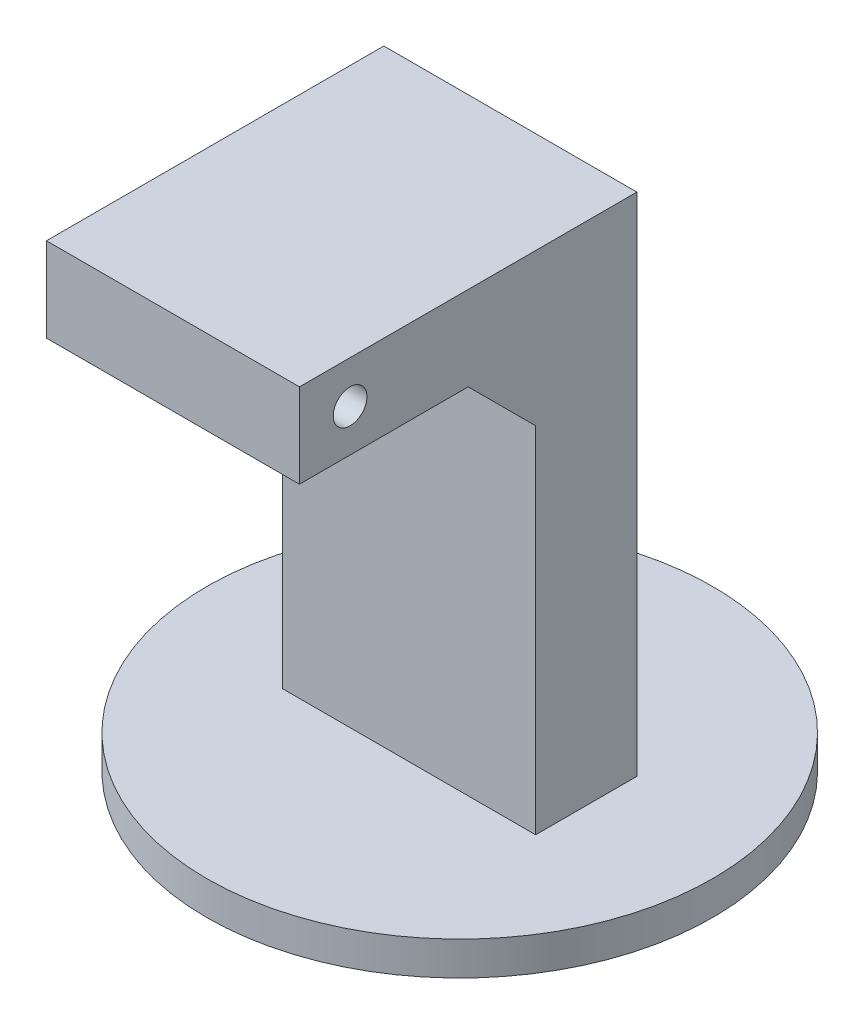
SolidWorks part; units mm, degrees
ref_plane "Front Plane" through (0, 0, 0) normal (0, 0, 1) x (1, 0, 0)
ref_plane "Top Plane" through (0, 0, 0) normal (0, 1, 0) x (1, 0, 0)
ref_plane "Right Plane" through (0, 0, 0) normal (1, 0, 0) x (0, 0, -1)
sketch "Sketch1" plane through (0, 0, 0) normal (0, 1, 0) x (1, 0, 0)
  circle A0 centre (0, 0) radius 15
  point P0 (0, 0)
  dimension "D1" = 30
extrude "Boss-Extrude1" add sketch "Sketch1" along normal blind 2
sketch "Sketch2" plane through (0, 2, 0) normal (0, 1, 0) x (1, 0, 0)
  line L1 (7.5, -3) -> (-7.5, -3)
  line L2 (7.5, -3) -> (7.5, 3)
  line L3 (7.5, 3) -> (-7.5, 3)
  line L4 (-7.5, -3) -> (-7.5, 3)
  line L5 (7.5, -3) -> (-7.5, 3) construction
  line L6 (7.5, 3) -> (-7.5, -3) construction
  point P0 (0, 0)
  dimension "D1" = 15
  dimension "D2" = 6
extrude "Boss-Extrude2" add sketch "Sketch2" along normal blind 25
sketch "Sketch3" plane through (0, 27, 0) normal (0, 1, 0) x (1, 0, 0)
  line L0 (7.5, -3) -> (7.5, 3) construction
  line L1 (-7.5, 3) -> (7.5, 3)
  line L2 (-7.5, 3) -> (-7.5, -17)
  line L3 (-7.5, -17) -> (7.5, -17)
  line L4 (7.5, 3) -> (7.5, -17)
  dimension "D1" = 20
extrude "Boss-Extrude3" add sketch "Sketch3" along normal blind 5
chamfer "Chamfer1" distance 4 angle 45 1 edges at (0, 27, 3)
sketch "Sketch4" plane through (7.5, 0, 0) normal (1, 0, 0) x (0, 0, -1)
  line L1 (-17, 32) -> (-17, 27) construction
  line L3 (-17, 32) -> (-17, 27) construction
  circle A0 centre (-14, 29.5) radius 1
  point P7 (-17, 29.5)
  dimension "D1" = 2
  dimension "D2" = 3
extrude "Cut-Extrude1" cut sketch "Sketch4" against normal up to surface (15 mm away) up to face at (-7.5, 20.7143, 5.8571)
